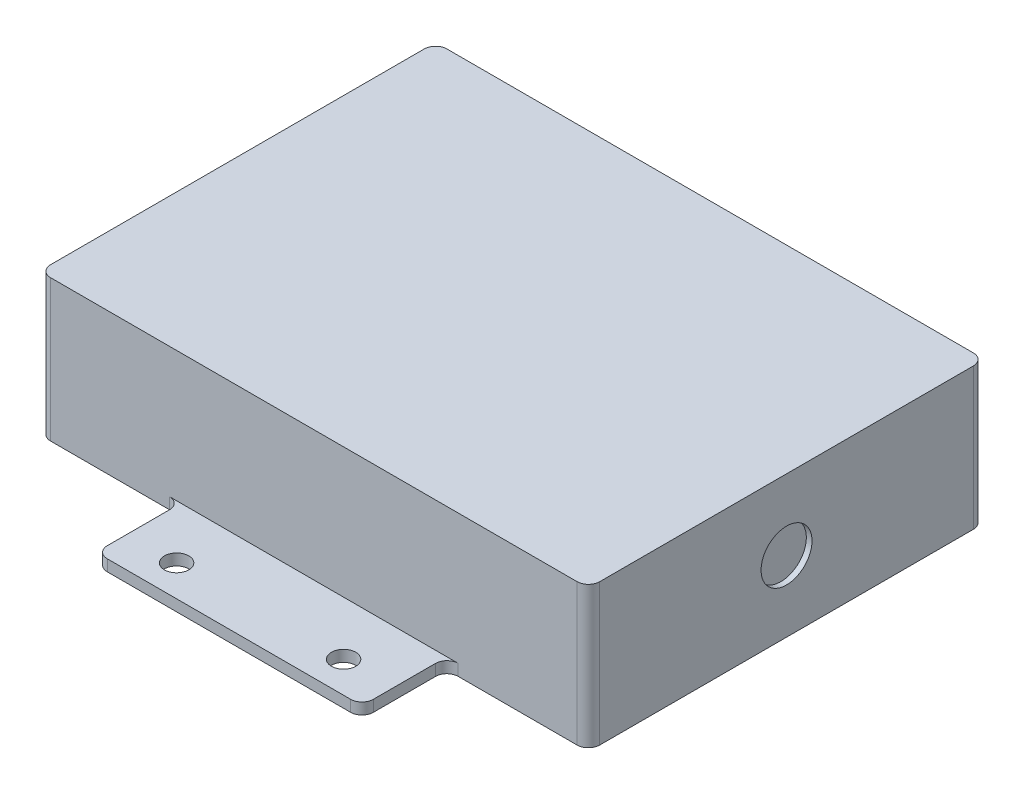
SolidWorks part; units mm, degrees
ref_plane "Front Plane" through (0, 0, 0) normal (0, 0, 1) x (1, 0, 0)
ref_plane "Top Plane" through (0, 0, 0) normal (0, 1, 0) x (1, 0, 0)
ref_plane "Right Plane" through (0, 0, 0) normal (1, 0, 0) x (0, 0, -1)
sketch "Sketch1" plane through (0, 0, 0) normal (0, 1, 0) x (1, 0, 0)
  line L1 (-48.5, -50) -> (48.5, -50)
  line L2 (-48.5, -50) -> (-48.5, 50)
  line L3 (-48.5, 50) -> (48.5, 50)
  line L4 (48.5, -50) -> (48.5, 50)
  line L5 (-48.5, -50) -> (48.5, 50) construction
  line L6 (-48.5, 50) -> (48.5, -50) construction
  point P0 (0, 0)
  dimension "D1" = 100
  dimension "D2" = 97
extrude "Boss-Extrude1" add sketch "Sketch1" along normal blind 25
sketch "Sketch2" plane through (0, 25, 0) normal (0, 1, 0) x (1, 0, 0)
  line L1 (-14.75, -44.5) -> (14.75, -44.5) construction
  line L2 (-14.75, -44.5) -> (-14.75, 44.5) construction
  line L3 (-14.75, 44.5) -> (14.75, 44.5) construction
  line L4 (14.75, -44.5) -> (14.75, 44.5) construction
  line L5 (-14.75, -44.5) -> (14.75, 44.5) construction
  line L6 (-14.75, 44.5) -> (14.75, -44.5) construction
  point P0 (0, 0)
  dimension "D1" = 89
  dimension "D2" = 29.5
hole_wizard "M4 Clearance Hole1" positions "Sketch3" profile "Sketch4" hole size "M4" standard "ANSI Metric" end condition through all
sketch "Sketch3" plane through (0, 25, 0) normal (0, 1, 0) x (1, 0, 0)
  point P0 (-14.75, 44.5)
  point P3 (14.75, 44.5)
  point P6 (-14.75, -44.5)
  point P9 (14.75, -44.5)
sketch "Sketch4" plane through (-14.75, 25, -44.5) normal (1, 0, 0) x (0, 0, 1)
  line L0 (0, 0) -> (0, 25)
  line L1 (0, 25) -> (2.15, 25)
  line L2 (2.15, 25) -> (2.15, 0)
  line L5 (2.15, 0) -> (0, 0)
  line L11 (0, -6.35) -> (0, 107.95) construction
  dimension "Thru Hole Dia." = 4.3
  dimension "Thru Hole Depth" = 25
sketch "Sketch5" plane through (-48.5, 0, 0) normal (-1, 0, 0) x (0, 0, 1)
  line L1 (-16, 7) -> (16, 7)
  line L2 (-16, 7) -> (-16, 20)
  line L3 (-16, 20) -> (16, 20)
  line L4 (16, 7) -> (16, 20)
  line L5 (-16, 7) -> (16, 20) construction
  line L6 (-16, 20) -> (16, 7) construction
  line L7 (-50, 0) -> (50, 0) construction
  point P0 (0, 13.5)
  dimension "D1" = 32
  dimension "D2" = 13
  dimension "D3" = 7
extrude "Cut-Extrude1" cut sketch "Sketch5" against normal blind 1
sketch "Sketch6" plane through (48.5, 0, 0) normal (1, 0, 0) x (0, 0, -1)
  line L0 (-50, 25) -> (-50, 0) construction
  circle A0 centre (0, 12.5) radius 4.5
  point P6 (-50, 12.5)
  dimension "D1" = 9
extrude "Cut-Extrude2" cut sketch "Sketch6" against normal blind 1
sketch "Sketch7" plane through (0, 25, 0) normal (0, 1, 0) x (1, 0, 0)
  line L0 (48.5, -50) -> (48.5, 50) construction
  line L1 (-48.5, 50) -> (48.5, 50)
  line L2 (-48.5, 50) -> (-48.5, 35)
  line L3 (-48.5, 35) -> (48.5, 35)
  line L4 (48.5, 50) -> (48.5, 35)
  line L6 (-48.5, -50) -> (48.5, -50)
  line L7 (-48.5, -50) -> (-48.5, -35)
  line L8 (-48.5, -35) -> (48.5, -35)
  line L9 (48.5, -50) -> (48.5, -35)
  dimension "D1" = 15
extrude "Cut-Extrude3" cut sketch "Sketch7" against normal offset from surface (23 mm away) 2 up to face at (-14.75, 0, 46.65)
sketch "Sketch8" plane through (0, 2, 0) normal (0, 1, 0) x (1, 0, 0)
  line L0 (-48.5, 35) -> (48.5, 35) construction
  line L1 (-48.5, 50) -> (-23.5, 50)
  line L2 (-48.5, 50) -> (-48.5, 35)
  line L3 (-48.5, 35) -> (-23.5, 35)
  line L4 (-23.5, 50) -> (-23.5, 35)
  line L5 (48.5, -35) -> (-48.5, -35) construction
  line L6 (48.5, 50) -> (23.5, 50)
  line L7 (48.5, 50) -> (48.5, 35)
  line L8 (48.5, 35) -> (23.5, 35)
  line L9 (23.5, 50) -> (23.5, 35)
  line L10 (-48.5, -50) -> (-23.5, -50)
  line L11 (-48.5, -50) -> (-48.5, -35)
  line L12 (-48.5, -35) -> (-23.5, -35)
  line L13 (-23.5, -50) -> (-23.5, -35)
  line L15 (48.5, -50) -> (23.5, -50)
  line L16 (48.5, -50) -> (48.5, -35)
  line L17 (48.5, -35) -> (23.5, -35)
  line L18 (23.5, -50) -> (23.5, -35)
  dimension "D1" = 25
extrude "Cut-Extrude4" cut sketch "Sketch8" against normal through all
fillet "Fillet1" radius 2 12 edges at (23.5, 1, -35) (23.5, 1, -50) (-23.5, 1, -50) (-23.5, 1, -35) (-48.5, 12.5, -35) (-48.5, 12.5, 35) (-23.5, 1, 35) (-23.5, 1, 50) (23.5, 1, 50) (23.5, 1, 35) (48.5, 12.5, -35) (48.5, 12.5, 35)
